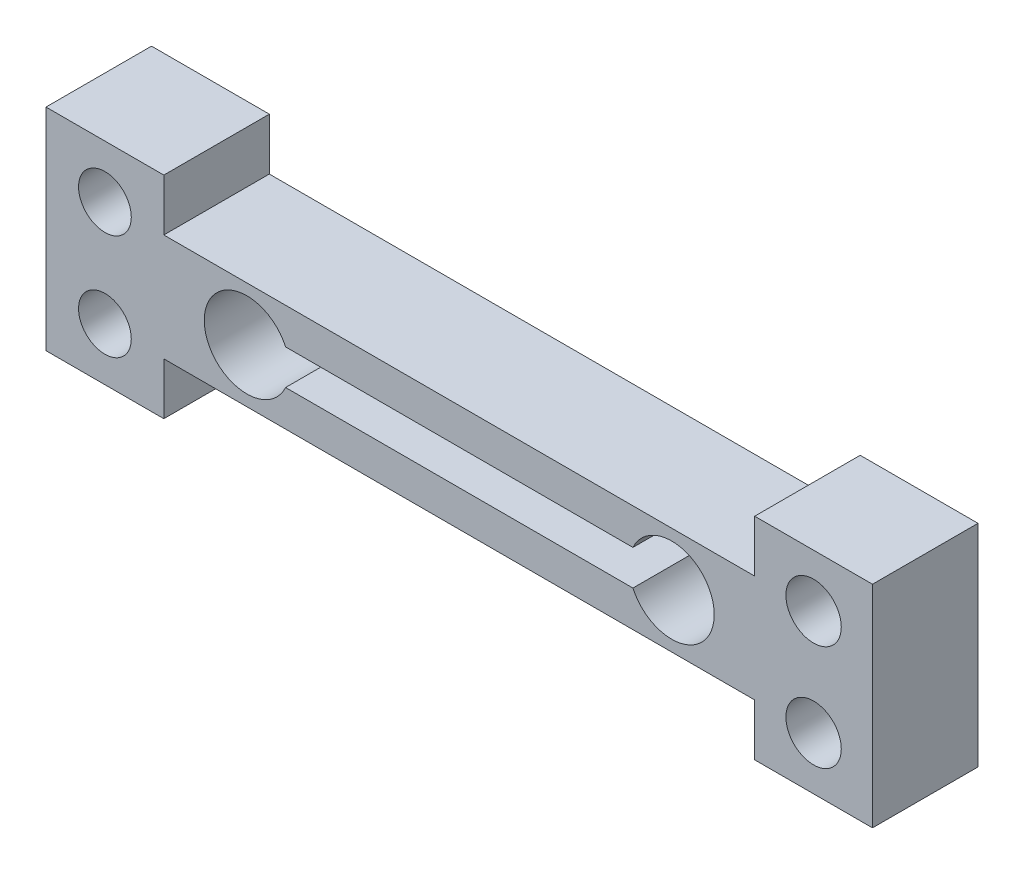
SolidWorks part; units mm, degrees
ref_plane "Front Plane" through (0, 0, 0) normal (0, 0, 1) x (1, 0, 0)
ref_plane "Top Plane" through (0, 0, 0) normal (0, 1, 0) x (1, 0, 0)
ref_plane "Right Plane" through (0, 0, 0) normal (1, 0, 0) x (0, 0, -1)
sketch "Sketch1" plane through (0, 0, 0) normal (0, 0, 1) x (1, 0, 0)
  line L0 (40.3, 3) -> (40.3, -3) construction
  line L1 (-3.35, 6) -> (3.35, 6)
  line L2 (-3.35, 6) -> (-3.35, -6)
  line L3 (-3.35, -6) -> (3.35, -6)
  line L4 (3.35, 6) -> (3.35, 3.05)
  line L5 (-3.35, 6) -> (3.35, -6) construction
  line L6 (-3.35, -6) -> (3.35, 6) construction
  line L7 (43.65, -6) -> (36.95, -6)
  line L8 (43.65, -6) -> (43.65, 6)
  line L9 (43.65, 6) -> (36.95, 6)
  line L10 (36.95, -6) -> (36.95, -3.05)
  line L11 (43.65, -6) -> (36.95, 6) construction
  line L12 (43.65, 6) -> (36.95, -6) construction
  line L13 (0, 3) -> (0, -3) construction
  line L14 (3.35, -3.05) -> (3.35, -6)
  line L15 (3.35, 3.05) -> (36.95, 3.05)
  line L17 (3.35, -3.05) -> (36.95, -3.05)
  line L19 (36.95, 3.05) -> (36.95, 6)
  line L20 (20.15, 3.05) -> (20.15, -3.05) construction
  circle A0 centre (40.3, 3) radius 1.575
  circle A1 centre (40.3, -3) radius 1.575
  circle A2 centre (0, 3) radius 1.5
  circle A3 centre (0, -3) radius 1.5
  point P0 (0, 0)
  point P6 (40.3, 0)
  point P15 (40.3, 0)
  point P17 (41.875, 3)
  point P20 (0, 0)
  point P24 (-1.5, 3)
  point P29 (20.15, 0)
  dimension "D5" = 3.15
  dimension "D6" = 6
  dimension "D7" = 3
  dimension "D8" = 6
  dimension "D1" = 12
  dimension "D2" = 6.7
  dimension "D3" = 47
  dimension "D4" = 6.7
  dimension "D9" = 6.1
extrude "Boss-Extrude1" add sketch "Sketch1" along normal mid plane 6
sketch "Sketch4" plane through (0, 0, 3) normal (0, 0, 1) x (1, 0, 0)
  line L0 (10.2737, 1) -> (30.0263, 1)
  line L1 (10.2737, -1) -> (30.0263, -1)
  line L2 (8.07, 0) -> (32.23, 0) construction
  line L3 (36.95, 3.05) -> (3.35, 3.05) construction
  arc A0 (10.2737, 1) -> (10.2737, -1) centre (8.07, 0) ccw
  arc A1 (30.0263, -1) -> (30.0263, 1) centre (32.23, 0) ccw
  point P8 (5.65, 0)
  point P9 (20.15, 0)
  point P10 (34.65, 0)
  point P11 (20.15, 3.05)
  point P12 (0, 0)
  point P15 (8.07, -0.0078)
  dimension "D1" = 4.84
  dimension "D2" = 1
  dimension "D3" = 2
  dimension "D4" = 29
extrude "Cut-Extrude1" cut sketch "Sketch4" against normal through all
